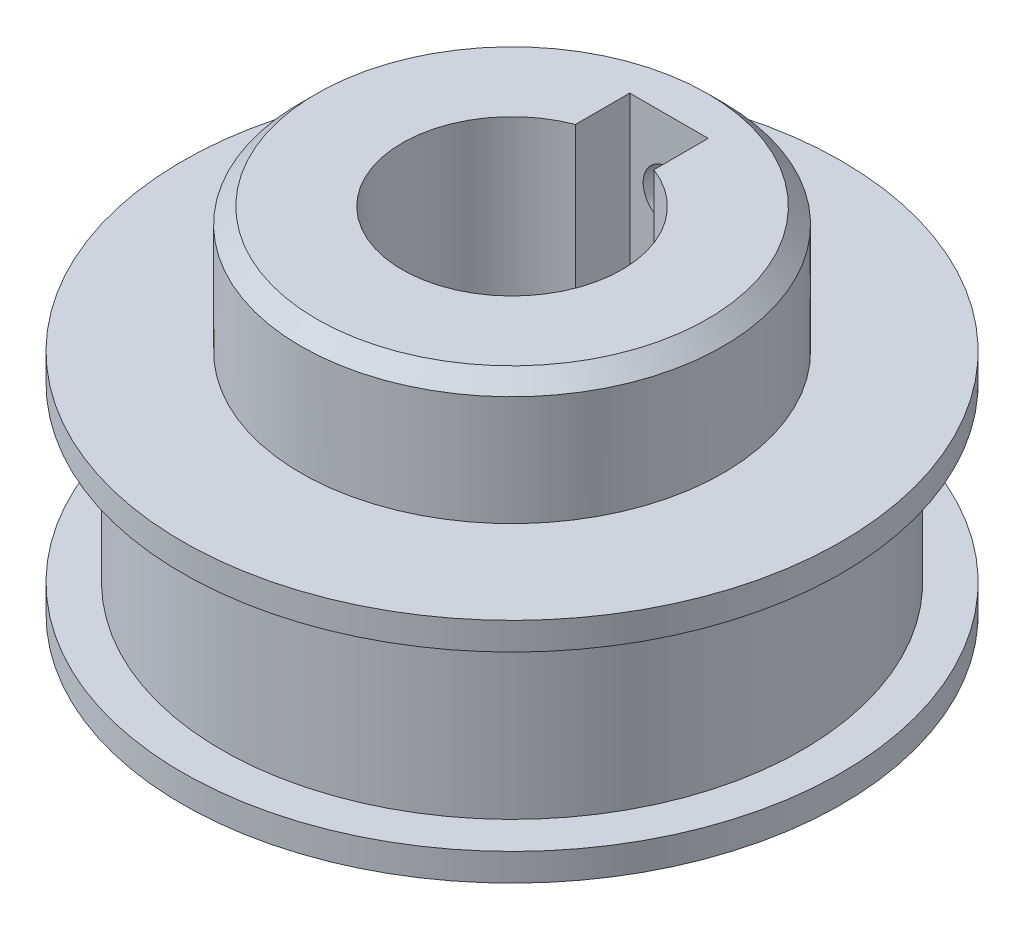
SolidWorks part; units mm, degrees
ref_plane "Piano frontale" through (0, 0, 0) normal (0, 0, 1) x (1, 0, 0)
ref_plane "Piano superiore" through (0, 0, 0) normal (0, 1, 0) x (1, 0, 0)
ref_plane "Piano destro" through (0, 0, 0) normal (1, 0, 0) x (0, 0, -1)
sketch "Schizzo1" plane through (0, 0, 0) normal (0, 0, 1) x (1, 0, 0)
  line L0 (0, 11.25) -> (13.45, 11.25)
  line L1 (13.45, 11.25) -> (13.45, 3.25)
  line L2 (13.45, 3.25) -> (21, 3.25)
  line L3 (21, 3.25) -> (21, 1.5)
  line L4 (21, 1.5) -> (18.5, 1.5)
  line L5 (18.5, 1.5) -> (18.5, -9.5)
  line L6 (18.5, -9.5) -> (21, -9.5)
  line L7 (21, -9.5) -> (21, -11.25)
  line L8 (21, -11.25) -> (0, -11.25)
  line L9 (0, -11.25) -> (0, 11.25)
  point P2 (21, 2.375)
  point P12 (0, 0)
  dimension "D1" = 13.45
  dimension "D2" = 21
  dimension "D3" = 18.5
  dimension "D4" = 11
  dimension "D5" = 22.5
  dimension "D6" = 8
ref_axis "Assi1" through (0, -12.375, 0) along (0, 1, 0)
revolve "Rivoluzione1" add sketch "Schizzo1" angle 360 about axis through (0, -12.375, 0) along (0, 1, 0)
chamfer "Smusso1" distance 1 angle 45 1 edges at (0, 11.25, -13.45)
sketch "Schizzo2" plane through (0, 11.25, 0) normal (0, 1, 0) x (1, 0, 0)
  circle A0 centre (0, 0) radius 6
  dimension "D1" = 12
extrude "Taglio-Estrusione1" cut sketch "Schizzo2" against normal through all
sketch "Schizzo3" plane through (0, 0, 0) normal (0, 0, 1) x (1, 0, 0)
  line L0 (13.45, 6.75) -> (-13.45, 6.75) construction
  line L1 (13.45, 3.25) -> (13.45, 10.25) construction
  line L2 (-13.45, 10.25) -> (-13.45, 3.25) construction
  circle A0 centre (0, 6.75) radius 1.65
  dimension "D1" = 3.3
extrude "Taglio-Estrusione2" cut sketch "Schizzo3" against normal through all
ref_plane "mezzeria_cinghia" through (0, -4, 0) normal (0, 1, 0) x (1, 0, 0)
sketch "Schizzo4" plane through (0, 11.25, 0) normal (0, 1, 0) x (1, 0, 0)
  circle A0 centre (0, 0) radius 7
  dimension "D1" = 14
extrude "Taglio-Estrusione3" cut sketch "Schizzo4" against normal through all
sketch "Schizzo5" plane through (0, 11.25, 0) normal (0, 1, 0) x (1, 0, 0)
  line L0 (0, 0) -> (0, 12.45) construction
  line L2 (2.5, 4) -> (-2.5, 4)
  line L3 (2.5, 4) -> (2.5, 10)
  line L4 (2.5, 10) -> (-2.5, 10)
  line L5 (-2.5, 4) -> (-2.5, 10)
  line L6 (2.5, 4) -> (-2.5, 10) construction
  line L7 (2.5, 10) -> (-2.5, 4) construction
  circle A0 centre (0, 0) radius 12.45 construction
  circle A1 centre (0, 0) radius 7 construction
  point P6 (0, 7)
  dimension "D1" = 5
  dimension "D2" = 3
extrude "Taglio-Estrusione4" cut sketch "Schizzo5" against normal through all
